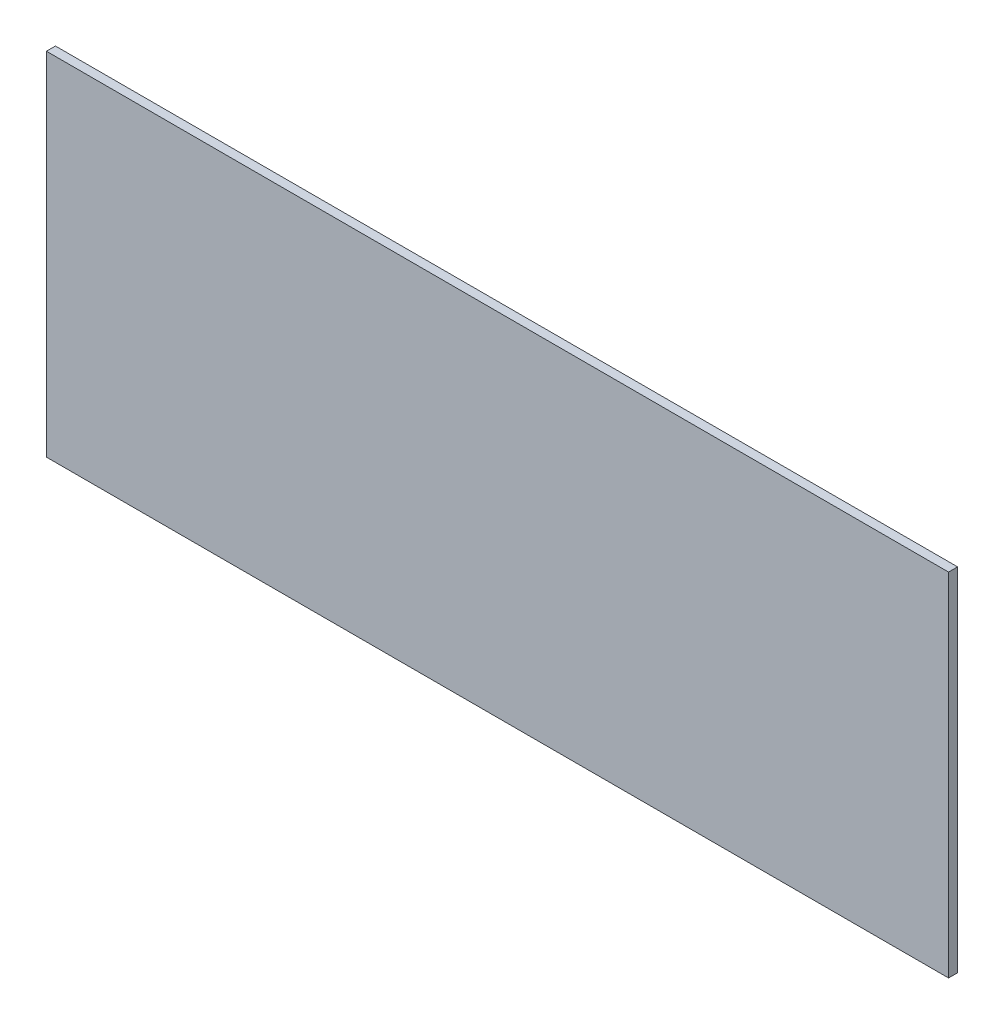
SolidWorks part; units mm, degrees
ref_plane "Front Plane" through (0, 0, 0) normal (0, 0, 1) x (1, 0, 0)
ref_plane "Top Plane" through (0, 0, 0) normal (0, 1, 0) x (1, 0, 0)
ref_plane "Right Plane" through (0, 0, 0) normal (1, 0, 0) x (0, 0, -1)
sketch "Sketch1" plane through (0, 0, 0) normal (0, 0, 1) x (1, 0, 0)
  line L1 (0, 0) -> (300, 0)
  line L2 (0, 0) -> (0, 116.9)
  line L3 (0, 116.9) -> (300, 116.9)
  line L4 (300, 0) -> (300, 116.9)
  dimension "D1" = 116.9
  dimension "D2" = 300
extrude "Boss-Extrude1" add sketch "Sketch1" along normal blind 3
